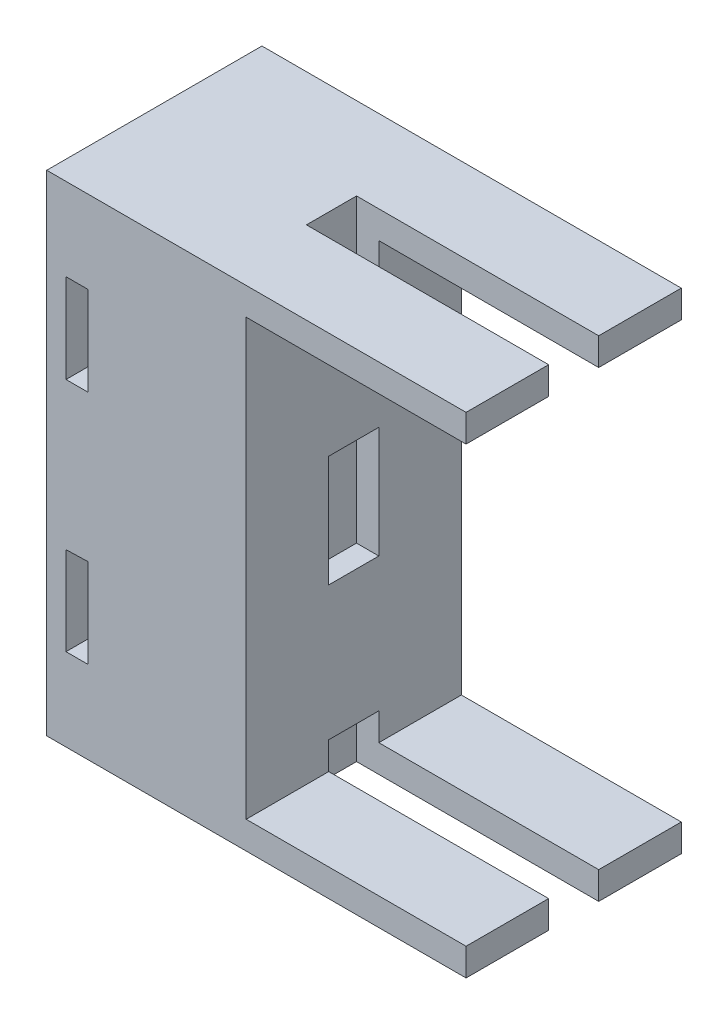
SolidWorks part; units mm, degrees
ref_plane "Front Plane" through (0, 0, 0) normal (0, 0, 1) x (1, 0, 0)
ref_plane "Top Plane" through (0, 0, 0) normal (0, 1, 0) x (1, 0, 0)
ref_plane "Right Plane" through (0, 0, 0) normal (1, 0, 0) x (0, 0, -1)
sketch "Sketch1" plane through (0, 0, 0) normal (0, 0, 1) x (1, 0, 0)
  line L0 (12.2551, 35.3123) -> (12.2551, 32.7723)
  line L5 (12.2551, 32.7723) -> (-8.0395, 32.7723)
  line L6 (-8.0395, 32.7723) -> (-8.0395, -7.3597)
  line L7 (-8.0395, -7.3597) -> (12.2551, -7.3597)
  line L8 (12.2551, -7.3597) -> (12.2551, -9.8997)
  line L9 (12.2551, -9.8997) -> (-10.0969, -9.8997)
  line L10 (-10.0969, -9.8997) -> (-10.0969, 35.3123)
  line L11 (-10.0969, 35.3123) -> (12.2551, 35.3123)
  dimension "D1" = 22.352
  dimension "D2" = 22.352
  dimension "D3" = 2.0574
  dimension "D4" = 40.132
  dimension "D5" = 2.54
  dimension "D6" = 2.54
extrude "Servo Clasper 2nd Half (Servo A)" add sketch "Sketch1" along normal blind 7.62
sketch "center encapsulator" plane through (0, 0, 0) normal (0, 0, 1) x (1, 0, 0)
  line L0 (-8.0395, -7.3597) -> (-8.0395, 32.7723) construction
  line L1 (-10.0969, 30.2958) -> (-8.0395, 30.2958)
  line L2 (-10.0969, 30.2958) -> (-10.0969, 17.8498)
  line L3 (-10.0969, 17.8498) -> (-8.0395, 17.8498)
  line L4 (-8.0395, 30.2958) -> (-8.0395, 17.8498)
  line L17 (-8.0395, 7.5628) -> (-10.0969, 7.5628)
  line L18 (-8.0395, 7.5628) -> (-8.0395, -4.8143)
  line L19 (-8.0395, -4.8143) -> (-10.0969, -4.8143)
  line L20 (-10.0969, 7.5628) -> (-10.0969, -4.8143)
  point P11 (-8.0395, 12.7063)
  dimension "D1" = 2.0574
  dimension "D2" = 2.0574
  dimension "D3" = 12.446
  dimension "D4" = 5.1435
  dimension "D5" = 5.1435
  dimension "D6" = 0
extrude "Cutout to hold servo" add sketch "center encapsulator" along normal blind 4.6228 from surface at 7.62 starting at face at (1.5935, 12.7063, 7.62)
sketch "Sketch7" plane through (0, 0, 0) normal (0, 0, 1) x (1, 0, 0)
  line L0 (12.2551, 35.3123) -> (12.2551, 32.7723)
  line L5 (12.2551, 32.7723) -> (-8.0395, 32.7723)
  line L6 (-8.0395, 32.7723) -> (-8.0395, -7.3597)
  line L7 (-8.0395, -7.3597) -> (12.2551, -7.3597)
  line L8 (12.2551, -7.3597) -> (12.2551, -9.8997)
  line L9 (12.2551, -9.8997) -> (-10.0969, -9.8997)
  line L10 (-10.0969, -9.8997) -> (-10.0969, 35.3123)
  line L11 (-10.0969, 35.3123) -> (12.2551, 35.3123)
  dimension "D1" = 22.352
  dimension "D2" = 22.352
  dimension "D3" = 2.0574
  dimension "D4" = 40.132
  dimension "D5" = 2.54
  dimension "D6" = 2.54
extrude "Servo Clasper 2nd Half (Other Servo)" add sketch "Sketch7" along normal blind 7.62 from surface at 12.2428 starting at face at (-9.0682, 24.0728, 12.2428)
sketch "Sketch8" plane through (0, 0, 0) normal (0, 0, 1) x (1, 0, 0)
  line L0 (-10.0969, 31.5023) -> (-8.0395, 31.5023)
  line L1 (-10.0969, 31.5023) -> (-10.0969, 23.8823)
  line L2 (-10.0969, 23.8823) -> (-8.0395, 23.8823)
  line L3 (-8.0395, 31.5023) -> (-8.0395, 23.8823)
  line L4 (-10.0969, 35.3123) -> (-10.0969, -9.8997) construction
  line L5 (12.2551, 35.3123) -> (-10.0969, 35.3123) construction
  point P6 (-9.0682, 31.5023)
  dimension "D1" = 0
  dimension "D2" = 3.81
  dimension "D3" = 7.62
sketch "Sketch10" plane through (0, 0, 0) normal (0, 0, 1) x (1, 0, 0)
  line L0 (2.6031, 35.5663) -> (2.6031, 33.0263)
  line L5 (2.6031, 33.0263) -> (-8.0395, 33.0263)
  line L6 (-8.0395, 33.0263) -> (-8.0395, -7.3597)
  line L7 (-8.0395, -7.3597) -> (2.6031, -7.3597)
  line L8 (2.6031, -7.3597) -> (2.6031, -9.8997)
  line L9 (2.6031, -9.8997) -> (-10.0969, -9.8997)
  line L10 (-10.0969, -9.8997) -> (-10.0969, 35.5663)
  line L11 (-10.0969, 35.5663) -> (2.6031, 35.5663)
  dimension "D1" = 12.7
  dimension "D2" = 12.7
  dimension "D3" = 2.0574
  dimension "D4" = 40.386
  dimension "D5" = 2.54
  dimension "D6" = 2.54
sketch "Sketch12" plane through (-10.0969, 0, 0) normal (-1, 0, 0) x (0, 0, 1)
  line L1 (0, 35.3123) -> (19.8628, 35.3123)
  line L2 (0, 35.3123) -> (0, -9.8997)
  line L3 (0, -9.8997) -> (19.8628, -9.8997)
  line L4 (19.8628, 35.3123) -> (19.8628, -9.8997)
extrude "Servo Holder Extrude" add sketch "Sketch12" along normal blind 16.35
sketch "Sketch13" plane through (0, 35.3123, 0) normal (0, 1, 0) x (1, 0, 0)
  line L0 (-10.0969, 0) -> (-8.0395, 0) construction
  line L5 (-19.2017, -7.6614) -> (-17.9137, -7.6614)
  line L6 (-19.2017, -7.6614) -> (-19.2017, -15.5354)
  line L7 (-19.2017, -15.5354) -> (-17.9137, -15.5354)
  line L8 (-18.4124, 0) -> (-15.3644, 0)
  line L9 (-18.4124, 0) -> (-18.4124, -33.528)
  line L10 (-18.4124, -33.528) -> (-15.3644, -33.528)
  line L11 (-15.3644, 0) -> (-15.3644, -33.528)
  line L12 (-17.9137, -7.6614) -> (-17.9137, -15.5354)
  dimension "D1" = 3.048
  dimension "D2" = 33.528
  dimension "D3" = 1.2879
  dimension "D4" = 7.874
  dimension "D5" = 0
sketch "Sketch14" plane through (-26.4469, 0, 0) normal (-1, 0, 0) x (0, 0, 1)
  line L0 (7.2961, 29.4703) -> (12.0586, 29.4703)
  line L2 (5.1689, 14.6875) -> (5.1689, 10.7251)
  line L6 (12.0586, 29.4703) -> (14.1859, 14.6875)
  line L7 (7.2961, -4.0577) -> (12.0586, -4.0577)
  line L8 (14.1859, 10.7251) -> (14.1859, 14.6875)
  line L9 (7.2961, 29.4703) -> (5.1689, 14.6875)
  line L10 (5.1689, 10.7251) -> (7.2961, -4.0577)
  line L11 (12.0586, -4.0577) -> (14.1859, 10.7251)
  line L12 (7.6614, 35.3123) -> (15.5354, 35.3123) construction
  dimension "D2" = 9.017
  dimension "D3" = 5.842
  dimension "D4" = 171.811
  dimension "D5" = 33.528
  dimension "D7" = 4.7625
  dimension "D8" = 3.9624
  dimension "D9" = 171.811
  dimension "D10" = 171.811
  dimension "D11" = 171.811
  dimension "D12" = 3.9624
extrude "Servo B Cut" cut sketch "Sketch14" against normal blind 7.62
sketch "Sketch18" plane through (0, 0, 0) normal (0, 0, -1) x (-1, 0, 0)
  line L1 (26.4469, 35.3123) -> (26.4469, -9.8997) construction
  line L5 (24.6689, 27.6923) -> (22.6369, 27.6923)
  line L6 (22.6369, 27.6923) -> (22.6369, 19.4765)
  line L7 (22.6369, 19.4765) -> (24.6689, 19.4765)
  line L8 (24.6689, 19.4765) -> (24.6689, 27.6923)
  line L11 (26.4469, -9.8997) -> (-12.2551, -9.8997) construction
  line L12 (-12.2551, 35.3123) -> (26.4469, 35.3123) construction
  line L13 (24.6689, 5.8746) -> (22.6369, 5.9361)
  line L14 (22.6369, 5.9361) -> (22.6369, -2.2797)
  line L15 (22.6369, -2.2797) -> (24.6689, -2.2797)
  line L16 (24.6689, -2.2797) -> (24.6689, 5.8746)
  dimension "D1" = 1.778
  dimension "D2" = 2.032
  dimension "D3" = 8.2158
  dimension "D4" = 7.62
  dimension "D5" = 8.2158
  dimension "D6" = 1.778
  dimension "D7" = 7.62
  dimension "D8" = 2.032
extrude "Servo B Securer Cut" cut sketch "Sketch18" against normal through all both
